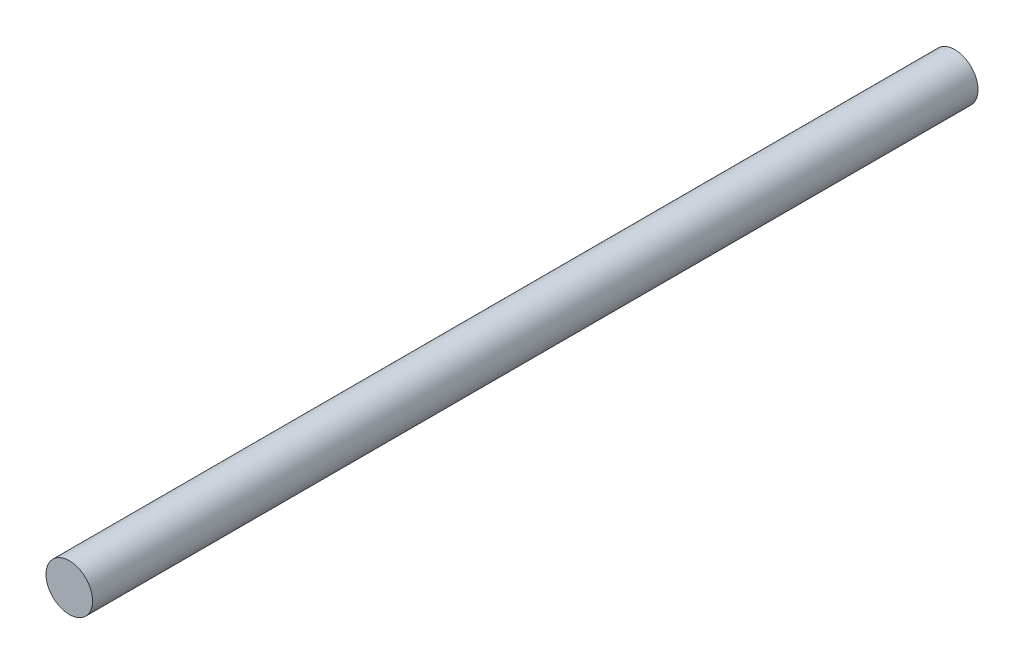
SolidWorks part; units mm, degrees
material "6061 Alloy"
ref_plane "Front Plane" through (0, 0, 0) normal (0, 0, 1) x (1, 0, 0)
ref_plane "Top Plane" through (0, 0, 0) normal (0, 1, 0) x (1, 0, 0)
ref_plane "Right Plane" through (0, 0, 0) normal (1, 0, 0) x (0, 0, -1)
sketch "Sketch1" plane through (0, 0, 0) normal (0, 0, 1) x (1, 0, 0)
  circle A0 centre (0, 0) radius 3.175
extrude "Boss-Extrude1" add sketch "Sketch1" along normal blind 120.65
